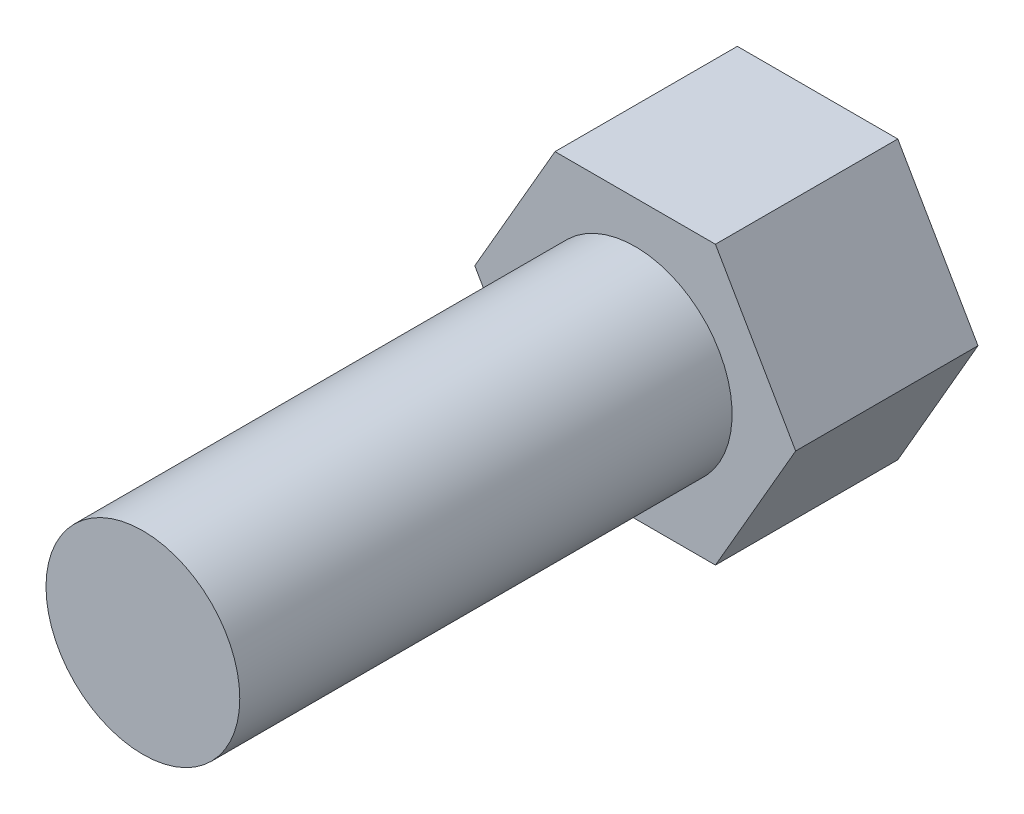
SolidWorks part; units mm, degrees
ref_plane "Front" through (0, 0, 0) normal (0, 0, 1) x (1, 0, 0)
ref_plane "Top" through (0, 0, 0) normal (0, 1, 0) x (1, 0, 0)
ref_plane "Right" through (0, 0, 0) normal (1, 0, 0) x (0, 0, -1)
other "Configuration Table"
sketch "Sketch1" plane through (0, 0, 0) normal (0, 0, 1) x (1, 0, 0)
  line L0 (0, 108.5945) -> (-13.208, 108.5945) construction
  line L1 (-2.4586, 104.7845) -> (-4.6583, 108.5945)
  line L2 (-4.6583, 108.5945) -> (-9.0577, 108.5945)
  line L3 (-9.0577, 108.5945) -> (-11.2574, 104.7845)
  line L4 (-11.2574, 104.7845) -> (-9.0577, 100.9745)
  line L5 (-9.0577, 100.9745) -> (-4.6583, 100.9745)
  line L6 (-4.6583, 100.9745) -> (-2.4586, 104.7845)
  line L7 (-13.208, 100.9745) -> (0, 100.9745) construction
  circle A0 centre (-6.858, 104.7845) radius 3.81 construction
extrude "Extrude1" add sketch "Sketch1" against normal blind 3.5 and the other way blind 1.5
sketch "Sketch2" plane through (0, 0, 1.5) normal (0, 0, 1) x (1, 0, 0)
  line L0 (-11.2574, 104.7845) -> (-2.4586, 104.7845) construction
  line L1 (-9.0577, 108.5945) -> (-4.6583, 100.9745) construction
  circle A0 centre (-6.858, 104.7845) radius 2.6568
extrude "Extrude2" add sketch "Sketch2" along normal blind 13.5
